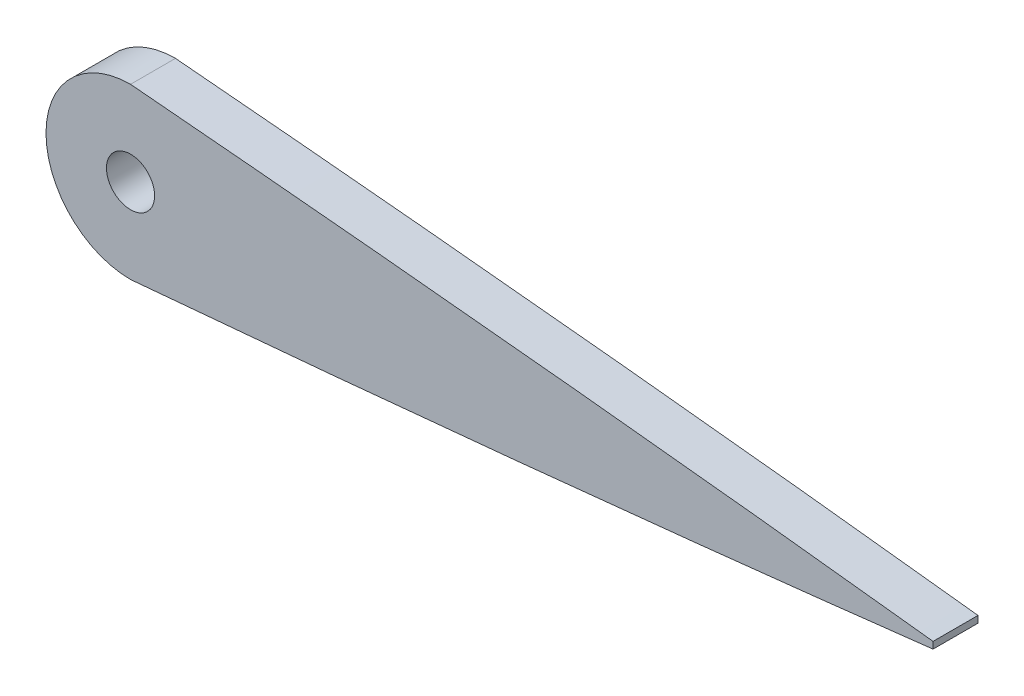
SolidWorks part; units mm, degrees
material "Фанера"
ref_plane "Спереди" through (0, 0, 0) normal (0, 0, 1) x (1, 0, 0)
ref_plane "Сверху" through (0, 0, 0) normal (0, 1, 0) x (1, 0, 0)
ref_plane "Справа" through (0, 0, 0) normal (1, 0, 0) x (0, 0, -1)
curve "Кривая1"
  spline degree 3 poles (200, 0.21, 0) (199.5201, 0.266, 0) (198.1795, 0.4223, 0) (195.7476, 0.7017, 0) (192.5308, 1.0651, 0) (188.7716, 1.4807, 0) (184.587, 1.9325, 0) (180.0562, 2.4092, 0) (175.2384, 2.9026, 0) (170.1814, 3.4057, 0) (164.925, 3.9132, 0) (159.5032, 4.4204, 0) (153.9461, 4.9234, 0) (148.2803, 5.4186, 0) (142.5299, 5.9028, 0) (136.7168, 6.3729, 0) (130.8615, 6.8262, 0) (124.9826, 7.2598, 0) (119.0976, 7.6711, 0) (113.2231, 8.0575, 0) (107.3746, 8.4163, 0) (101.5666, 8.7448, 0) (95.8133, 9.0407, 0) (90.1279, 9.3014, 0) (84.5231, 9.5247, 0) (79.0111, 9.7082, 0) (73.6037, 9.85, 0) (68.3121, 9.9482, 0) (63.1472, 10.0012, 0) (58.1196, 10.0077, 0) (53.2393, 9.9665, 0) (48.5164, 9.8771, 0) (43.9603, 9.7388, 0) (39.5803, 9.5517, 0) (35.3856, 9.3161, 0) (31.3849, 9.0325, 0) (27.5868, 8.7017, 0) (23.9997, 8.3252, 0) (20.6317, 7.9043, 0) (17.4909, 7.4408, 0) (14.5849, 6.9366, 0) (11.9213, 6.3939, 0) (9.5074, 5.8148, 0) (7.3502, 5.2016, 0) (5.4564, 4.5565, 0) (3.8315, 3.8815, 0) (2.4822, 3.178, 0) (1.4075, 2.4454, 0) (0.6238, 1.6789, 0) (0.1006, 0.8638, 0) (0.0324, 0.2785, 0) (0, 0, 0) knots 0 0 0 0 0.007145 0.019956 0.036196 0.055011 0.075879 0.098429 0.122376 0.147488 0.173572 0.20046 0.228005 0.256076 0.284555 0.313333 0.34231 0.371393 0.400496 0.429538 0.458442 0.487136 0.515552 0.543624 0.57129 0.598491 0.62517 0.651272 0.676746 0.701542 0.725611 0.748908 0.771388 0.793008 0.813728 0.833508 0.85231 0.870097 0.886836 0.902493 0.917037 0.930441 0.94268 0.953734 0.96359 0.972247 0.979722 0.986065 0.991385 0.995901 1 1 1 1
curve "Кривая2"
  spline degree 3 poles (0, 0, 0) (0.0324, -0.2785, 0) (0.1006, -0.8638, 0) (0.6238, -1.6789, 0) (1.4075, -2.4454, 0) (2.4822, -3.178, 0) (3.8315, -3.8815, 0) (5.4564, -4.5565, 0) (7.3502, -5.2016, 0) (9.5074, -5.8148, 0) (11.9213, -6.3939, 0) (14.5849, -6.9366, 0) (17.4909, -7.4408, 0) (20.6317, -7.9043, 0) (23.9997, -8.3252, 0) (27.5868, -8.7017, 0) (31.3849, -9.0325, 0) (35.3856, -9.3161, 0) (39.5803, -9.5517, 0) (43.9603, -9.7388, 0) (48.5164, -9.8771, 0) (53.2393, -9.9665, 0) (58.1196, -10.0077, 0) (63.1472, -10.0012, 0) (68.3121, -9.9482, 0) (73.6037, -9.85, 0) (79.0111, -9.7082, 0) (84.5231, -9.5247, 0) (90.1279, -9.3014, 0) (95.8133, -9.0407, 0) (101.5666, -8.7448, 0) (107.3746, -8.4163, 0) (113.2231, -8.0575, 0) (119.0976, -7.6711, 0) (124.9826, -7.2598, 0) (130.8615, -6.8262, 0) (136.7168, -6.3729, 0) (142.5299, -5.9028, 0) (148.2803, -5.4186, 0) (153.9461, -4.9234, 0) (159.5032, -4.4204, 0) (164.925, -3.9132, 0) (170.1814, -3.4057, 0) (175.2384, -2.9026, 0) (180.0562, -2.4092, 0) (184.587, -1.9325, 0) (188.7716, -1.4807, 0) (192.5308, -1.0651, 0) (195.7476, -0.7017, 0) (198.1795, -0.4223, 0) (199.5201, -0.266, 0) (200, -0.21, 0) knots 0 0 0 0 0.004099 0.008615 0.013935 0.020278 0.027753 0.03641 0.046266 0.05732 0.069559 0.082963 0.097507 0.113164 0.129903 0.14769 0.166492 0.186272 0.206992 0.228612 0.251092 0.274389 0.298458 0.323254 0.348728 0.37483 0.401509 0.42871 0.456376 0.484448 0.512864 0.541558 0.570462 0.599504 0.628607 0.65769 0.686667 0.715445 0.743924 0.771995 0.79954 0.826428 0.852512 0.877624 0.901571 0.924121 0.944989 0.963804 0.980044 0.992855 1 1 1 1
sketch "Эскиз3" plane through (0, 0, 0) normal (0, 0, 1) x (1, 0, 0)
  line L0 (200, 0.21) -> (200, -0.21)
  line L1 (63.6, 9.9908) -> (63.6, 6.9656)
  line L2 (63.6, 6.9656) -> (66.4, 6.9656)
  line L3 (66.4, 6.9656) -> (66.4, 9.9656)
  line L4 (97.6, -8.9469) -> (97.6, -5.8023)
  line L5 (97.6, -5.8023) -> (100.4, -5.8023)
  line L6 (100.4, -5.8023) -> (100.4, -8.8023)
  line L7 (124, 7.3263) -> (124, 4.1244)
  line L8 (124, 4.1244) -> (126.8, 4.1244)
  line L9 (126.8, 4.1244) -> (126.8, 7.1244)
  circle A0 centre (109, 0) radius 4
  circle A1 centre (55, 0) radius 4
  arc A2 (150, 5.2672) -> (150, -5.2672) centre (150, 0) ccw
  arc A3 (142.8327, 5.8745) -> (142.8327, -5.8745) centre (150, 0) ccw
  circle A4 centre (150, 0) radius 1.5
  spline S0 degree 3 poles (-10483.672, -3294.1453) (181.4835, 90.2828) (-8.6097, 12.7072) (0.6238, -1.6789) (1.4075, -2.4454) (2.4822, -3.178) (3.8315, -3.8815) (5.4564, -4.5565) (7.3502, -5.2016) (9.5074, -5.8148) (11.9213, -6.3939) (14.5849, -6.9366) (17.4909, -7.4408) (20.6317, -7.9043) (23.9997, -8.3252) (27.5868, -8.7017) (31.3849, -9.0325) (35.3856, -9.3161) (39.5803, -9.5517) (43.9603, -9.7388) (48.5164, -9.8771) (53.2393, -9.9665) (58.1196, -10.0077) (63.1472, -10.0012) (68.3121, -9.9482) (73.6037, -9.85) (79.0111, -9.7082) (84.5231, -9.5247) (90.1279, -9.3014) (95.8133, -9.0407) (101.5666, -8.7448) (107.3746, -8.4163) (113.2231, -8.0575) (119.0976, -7.6711) (124.9826, -7.2598) (130.8615, -6.8262) (136.7168, -6.3729) (142.5299, -5.9028) (148.2803, -5.4186) (153.9461, -4.9234) (161.2601, -4.2614) (168.3719, -3.5857) (175.2384, -2.9026) (180.0562, -2.4092) (184.587, -1.9325) (188.7716, -1.4807) (192.5308, -1.0651) (195.7476, -0.7017) (358.0703, 17.9461) (515.4385, 69.7392) (1945.0854, -10842.3765) knots -0.232007 -0.232007 -0.232007 -0.232007 0.004099 0.008615 0.013935 0.020278 0.027753 0.03641 0.046266 0.05732 0.069559 0.082963 0.097507 0.113164 0.129903 0.14769 0.166492 0.186272 0.206992 0.228612 0.251092 0.274389 0.298458 0.323254 0.348728 0.37483 0.401509 0.42871 0.456376 0.484448 0.512864 0.541558 0.570462 0.599504 0.628607 0.65769 0.686667 0.715445 0.743924 0.771995 0.79954 0.852512 0.877624 0.901571 0.924121 0.944989 0.963804 0.980044 0.992855 3.37973 3.37973 3.37973 3.37973 only from (0, 0) to (200, -0.21) construction
  spline S1 degree 3 poles (2585.5438, 15799.795) (556.9762, -84.0137) (379.3837, -20.3946) (195.7476, 0.7017) (192.5308, 1.0651) (188.7716, 1.4807) (184.587, 1.9325) (180.0562, 2.4092) (175.2384, 2.9026) (168.3719, 3.5857) (161.2601, 4.2614) (153.9461, 4.9234) (148.2803, 5.4186) (142.5299, 5.9028) (136.7168, 6.3729) (130.8615, 6.8262) (124.9826, 7.2598) (119.0976, 7.6711) (113.2231, 8.0575) (107.3746, 8.4163) (101.5666, 8.7448) (95.8133, 9.0407) (90.1279, 9.3014) (84.5231, 9.5247) (79.0111, 9.7082) (73.6037, 9.85) (68.3121, 9.9482) (63.1472, 10.0012) (58.1196, 10.0077) (53.2393, 9.9665) (48.5164, 9.8771) (43.9603, 9.7388) (39.5803, 9.5517) (35.3856, 9.3161) (31.3849, 9.0325) (27.5868, 8.7017) (23.9997, 8.3252) (20.6317, 7.9043) (17.4909, 7.4408) (14.5849, 6.9366) (11.9213, 6.3939) (9.5074, 5.8148) (7.3502, 5.2016) (5.4564, 4.5565) (3.8315, 3.8815) (2.4822, 3.178) (1.4075, 2.4454) (0.6238, 1.6789) (-9.766, -14.5088) (233.4099, -111.1825) (-15235.9163, 4803.1017) knots -2.696946 -2.696946 -2.696946 -2.696946 0.007145 0.019956 0.036196 0.055011 0.075879 0.098429 0.122376 0.147488 0.20046 0.228005 0.256076 0.284555 0.313333 0.34231 0.371393 0.400496 0.429538 0.458442 0.487136 0.515552 0.543624 0.57129 0.598491 0.62517 0.651272 0.676746 0.701542 0.725611 0.748908 0.771388 0.793008 0.813728 0.833508 0.85231 0.870097 0.886836 0.902493 0.917037 0.930441 0.94268 0.953734 0.96359 0.972247 0.979722 0.986065 0.991385 0.995901 1.262807 1.262807 1.262807 1.262807 only from (200, 0.21) to (0, 0) construction
  spline S2 degree 3 poles (0, 0) (0.0324, -0.2785) (0.1006, -0.8638) (0.6238, -1.6789) (1.4075, -2.4454) (2.4822, -3.178) (3.8315, -3.8815) (5.4564, -4.5565) (7.3502, -5.2016) (9.5074, -5.8148) (11.9213, -6.3939) (14.5849, -6.9366) (17.4909, -7.4408) (20.6317, -7.9043) (23.9997, -8.3252) (27.5868, -8.7017) (31.3849, -9.0325) (35.3856, -9.3161) (39.5803, -9.5517) (43.9603, -9.7388) (48.5164, -9.8771) (53.2393, -9.9665) (58.1196, -10.0077) (63.1472, -10.0012) (68.3121, -9.9482) (73.6037, -9.85) (79.0111, -9.7082) (84.5231, -9.5247) (90.1279, -9.3014) (94.497, -9.1011) (96.9966, -8.9773) (97.6, -8.9469) knots 0 0 0 0 0.004099 0.008615 0.013935 0.020278 0.027753 0.03641 0.046266 0.05732 0.069559 0.082963 0.097507 0.113164 0.129903 0.14769 0.166492 0.186272 0.206992 0.228612 0.251092 0.274389 0.298458 0.323254 0.348728 0.37483 0.401509 0.42871 0.456376 0.484448 0.493381 0.493381 0.493381 0.493381
  spline S3 degree 3 poles (200, 0.21) (199.5201, 0.266) (198.1795, 0.4223) (195.7476, 0.7017) (192.5308, 1.0651) (188.7716, 1.4807) (184.587, 1.9325) (180.0562, 2.4092) (175.2384, 2.9026) (168.3719, 3.5857) (161.2601, 4.2614) (153.9461, 4.9234) (148.2803, 5.4186) (142.5299, 5.9028) (136.7168, 6.3729) (131.4667, 6.7793) (128.1563, 7.0254) (126.8, 7.1244) knots 0 0 0 0 0.007145 0.019956 0.036196 0.055011 0.075879 0.098429 0.122376 0.147488 0.20046 0.228005 0.256076 0.284555 0.313333 0.34231 0.362417 0.362417 0.362417 0.362417
  spline S4 degree 3 poles (63.6, 9.9908) (63.4338, 9.9918) (61.5906, 10.0032) (58.1196, 10.0077) (53.2393, 9.9665) (48.5164, 9.8771) (43.9603, 9.7388) (39.5803, 9.5517) (35.3856, 9.3161) (31.3849, 9.0325) (27.5868, 8.7017) (23.9997, 8.3252) (20.6317, 7.9043) (17.4909, 7.4408) (14.5849, 6.9366) (11.9213, 6.3939) (9.5074, 5.8148) (7.3502, 5.2016) (5.4564, 4.5565) (3.8315, 3.8815) (2.4822, 3.178) (1.4075, 2.4454) (0.6238, 1.6789) (0.1006, 0.8638) (0.0324, 0.2785) (0, 0) knots 0.674288 0.674288 0.674288 0.674288 0.676746 0.701542 0.725611 0.748908 0.771388 0.793008 0.813728 0.833508 0.85231 0.870097 0.886836 0.902493 0.917037 0.930441 0.94268 0.953734 0.96359 0.972247 0.979722 0.986065 0.991385 0.995901 1 1 1 1
  spline S5 degree 3 poles (100.4, -8.8023) (100.7825, -8.782) (103.1029, -8.6579) (107.3746, -8.4163) (113.2231, -8.0575) (119.0976, -7.6711) (124.9826, -7.2598) (130.8615, -6.8262) (136.7168, -6.3729) (142.5299, -5.9028) (148.2803, -5.4186) (153.9461, -4.9234) (161.2601, -4.2614) (168.3719, -3.5857) (175.2384, -2.9026) (180.0562, -2.4092) (184.587, -1.9325) (188.7716, -1.4807) (192.5308, -1.0651) (195.7476, -0.7017) (198.1795, -0.4223) (199.5201, -0.266) (200, -0.21) knots 0.5072 0.5072 0.5072 0.5072 0.512864 0.541558 0.570462 0.599504 0.628607 0.65769 0.686667 0.715445 0.743924 0.771995 0.79954 0.852512 0.877624 0.901571 0.924121 0.944989 0.963804 0.980044 0.992855 1 1 1 1
  spline S6 degree 3 poles (124, 7.3263) (122.3646, 7.4427) (118.7696, 7.6927) (113.2231, 8.0575) (107.3746, 8.4163) (101.5666, 8.7448) (95.8133, 9.0407) (90.1279, 9.3014) (84.5231, 9.5247) (79.0111, 9.7082) (73.6037, 9.85) (69.4115, 9.9278) (67.0232, 9.9585) (66.4, 9.9656) knots 0.376253 0.376253 0.376253 0.376253 0.400496 0.429538 0.458442 0.487136 0.515552 0.543624 0.57129 0.598491 0.62517 0.651272 0.660487 0.660487 0.660487 0.660487
  point P17 (65, 6.9656)
  point P20 (99, -5.8023)
  dimension "D1" = 8
  dimension "D2" = 8
  dimension "D16" = 5.2672
  dimension "D17" = 9.2672
  dimension "D18" = 3
  dimension "D3" = 109
  dimension "D4" = 55
  dimension "D5" = 2.8
  dimension "D6" = 2.8
  dimension "D7" = 2.8
  dimension "D8" = 10
  dimension "D9" = 10
  dimension "D10" = 15
  dimension "D11" = 3
  dimension "D12" = 3
  dimension "D13" = 3
  dimension "D14" = 150
  dimension "D15" = 10.5344
extrude "Бобышка-Вытянуть1" add sketch "Эскиз3" along normal mid plane 2.8 contours A2 S5 L0 S3 A4
equation "\"D16@Эскиз3\"=\"D15@Эскиз3\"/2"
equation "\"D17@Эскиз3\"=\"D16@Эскиз3\"+4"
